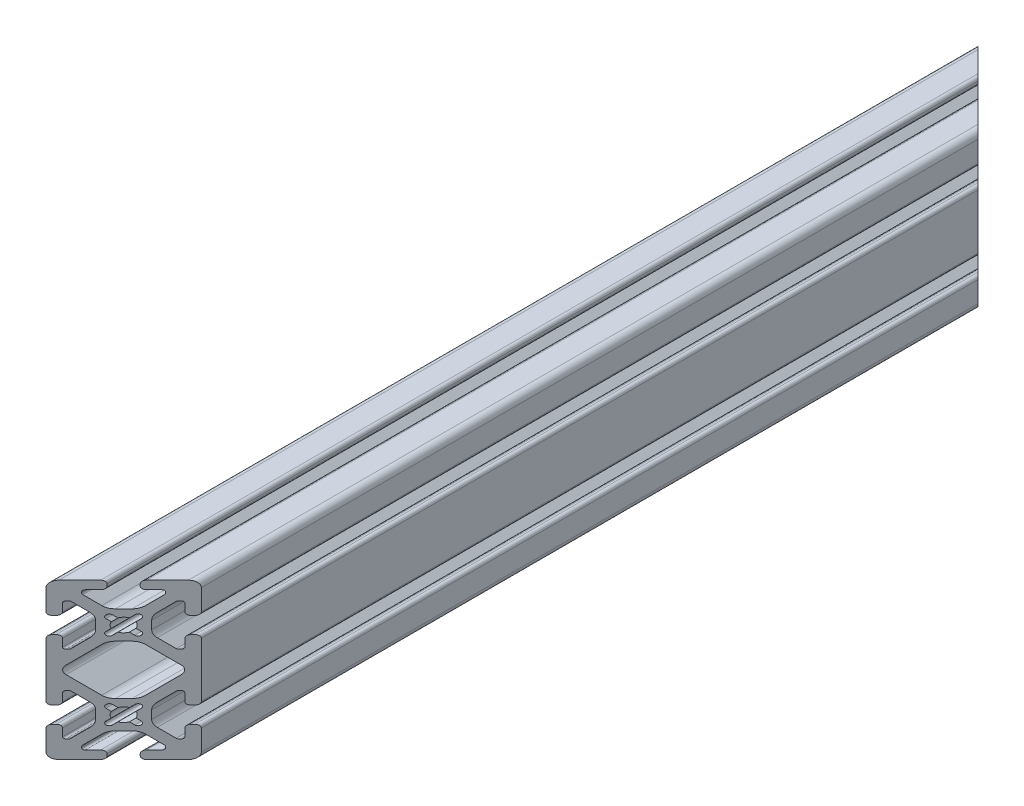
SolidWorks part; units mm, degrees
material "6063-T6"
ref_plane "Front Plane" through (0, 0, 0) normal (0, 0, 1) x (1, 0, 0)
ref_plane "Top Plane" through (0, 0, 0) normal (0, 1, 0) x (1, 0, 0)
ref_plane "Right Plane" through (0, 0, 0) normal (1, 0, 0) x (0, 0, -1)
ref_plane "Plane1" through (0, 0, -25.4) normal (0, 0, -1) x (-1, 0, 0)
sketch "Sketch1" plane through (0, 0, -25.4) normal (0, 0, -1) x (-1, 0, 0)
  line L0 (5.3872, 29.8392) -> (14.1109, 21.1155)
  line L1 (14.1109, 16.9845) -> (5.3872, 8.2608)
  line L2 (2.0285, 6.8697) -> (-2.0285, 6.8697)
  line L3 (-5.3872, 8.2608) -> (-14.1109, 16.9845)
  line L4 (-14.1109, 21.1155) -> (-5.3872, 29.8392)
  line L5 (-2.0285, 31.2303) -> (2.0285, 31.2303)
  line L6 (1.4014, 3.0179) -> (2.7269, 4.3433)
  line L7 (4.3433, 2.7269) -> (3.0179, 1.4014)
  line L8 (3.0179, -1.4014) -> (4.3433, -2.7269)
  line L9 (2.7269, -4.3433) -> (1.4014, -3.0179)
  line L10 (-1.4014, -3.0179) -> (-2.7269, -4.3433)
  line L11 (-4.3433, -2.7269) -> (-3.0179, -1.4014)
  line L12 (-3.0179, 1.4014) -> (-4.3433, 2.7269)
  line L13 (-2.7269, 4.3433) -> (-1.4014, 3.0179)
  line L14 (3.0179, 36.6986) -> (4.3433, 35.3731)
  line L15 (2.7269, 33.7567) -> (1.4014, 35.0821)
  line L16 (-1.4014, 35.0821) -> (-2.7269, 33.7567)
  line L17 (-4.3433, 35.3731) -> (-3.0179, 36.6986)
  line L18 (-3.0179, 39.5014) -> (-4.3433, 40.8269)
  line L19 (-2.7269, 42.4433) -> (-1.4014, 41.1179)
  line L20 (1.4014, 41.1179) -> (2.7269, 42.4433)
  line L21 (4.3433, 40.8269) -> (3.0179, 39.5014)
  line L22 (17.4752, 34.036) -> (16.5608, 34.036)
  line L23 (14.986, 32.4612) -> (14.986, 28.702)
  line L24 (14.097, 27.813) -> (13.5289, 27.813)
  line L25 (12.9003, 28.0734) -> (8.2608, 32.7128)
  line L26 (6.8697, 36.0715) -> (6.8697, 40.1285)
  line L27 (8.2608, 43.4872) -> (12.9003, 48.1266)
  line L28 (13.5289, 48.387) -> (14.097, 48.387)
  line L29 (14.986, 47.498) -> (14.986, 43.7388)
  line L30 (16.5608, 42.164) -> (17.4752, 42.164)
  line L31 (19.05, 43.7388) -> (19.05, 53.975)
  line L32 (15.875, 57.15) -> (5.6388, 57.15)
  line L33 (4.064, 55.5752) -> (4.064, 54.6608)
  line L34 (5.6388, 53.086) -> (9.398, 53.086)
  line L35 (10.287, 52.197) -> (10.287, 51.6289)
  line L36 (10.0266, 51.0003) -> (5.3872, 46.3608)
  line L37 (2.0285, 44.9697) -> (-2.0285, 44.9697)
  line L38 (-5.3872, 46.3608) -> (-10.0266, 51.0003)
  line L39 (-10.287, 51.6289) -> (-10.287, 52.197)
  line L40 (-9.398, 53.086) -> (-5.6388, 53.086)
  line L41 (-4.064, 54.6608) -> (-4.064, 55.5752)
  line L42 (-5.6388, 57.15) -> (-15.875, 57.15)
  line L43 (-19.05, 53.975) -> (-19.05, 43.7388)
  line L44 (-17.4752, 42.164) -> (-16.5608, 42.164)
  line L45 (-14.986, 43.7388) -> (-14.986, 47.498)
  line L46 (-14.097, 48.387) -> (-13.5289, 48.387)
  line L47 (-12.9003, 48.1266) -> (-8.2608, 43.4872)
  line L48 (-6.8697, 40.1285) -> (-6.8697, 36.0715)
  line L49 (-8.2608, 32.7128) -> (-12.9003, 28.0734)
  line L50 (-13.5289, 27.813) -> (-14.097, 27.813)
  line L51 (-14.986, 28.702) -> (-14.986, 32.4612)
  line L52 (-16.5608, 34.036) -> (-17.4752, 34.036)
  line L53 (-19.05, 32.4612) -> (-19.05, 5.6388)
  line L54 (-17.4752, 4.064) -> (-16.5608, 4.064)
  line L55 (-14.986, 5.6388) -> (-14.986, 9.398)
  line L56 (-14.097, 10.287) -> (-13.5289, 10.287)
  line L57 (-12.9003, 10.0266) -> (-8.2608, 5.3872)
  line L58 (-6.8697, 2.0285) -> (-6.8697, -2.0285)
  line L59 (-8.2608, -5.3872) -> (-12.9003, -10.0266)
  line L60 (-13.5289, -10.287) -> (-14.097, -10.287)
  line L61 (-14.986, -9.398) -> (-14.986, -5.6388)
  line L62 (-16.5608, -4.064) -> (-17.4752, -4.064)
  line L63 (-19.05, -5.6388) -> (-19.05, -15.875)
  line L64 (-15.875, -19.05) -> (-5.6388, -19.05)
  line L65 (-4.064, -17.4752) -> (-4.064, -16.5608)
  line L66 (-5.6388, -14.986) -> (-9.398, -14.986)
  line L67 (-10.287, -14.097) -> (-10.287, -13.5289)
  line L68 (-10.0266, -12.9003) -> (-5.3872, -8.2608)
  line L69 (-2.0285, -6.8697) -> (2.0285, -6.8697)
  line L70 (5.3872, -8.2608) -> (10.0266, -12.9003)
  line L71 (10.287, -13.5289) -> (10.287, -14.097)
  line L72 (9.398, -14.986) -> (5.6388, -14.986)
  line L73 (4.064, -16.5608) -> (4.064, -17.4752)
  line L74 (5.6388, -19.05) -> (15.875, -19.05)
  line L75 (19.05, -15.875) -> (19.05, -5.6388)
  line L76 (17.4752, -4.064) -> (16.5608, -4.064)
  line L77 (14.986, -5.6388) -> (14.986, -9.398)
  line L78 (14.097, -10.287) -> (13.5289, -10.287)
  line L79 (12.9003, -10.0266) -> (8.2608, -5.3872)
  line L80 (6.8697, -2.0285) -> (6.8697, 2.0285)
  line L81 (8.2608, 5.3872) -> (12.9003, 10.0266)
  line L82 (13.5289, 10.287) -> (14.097, 10.287)
  line L83 (14.986, 9.398) -> (14.986, 5.6388)
  line L84 (16.5608, 4.064) -> (17.4752, 4.064)
  line L85 (19.05, 5.6388) -> (19.05, 32.4612)
  arc A0 (14.1109, 21.1155) -> (14.1109, 16.9845) centre (12.0454, 19.05) cw
  arc A1 (5.3872, 8.2608) -> (2.0285, 6.8697) centre (2.0285, 11.6195) cw
  arc A2 (-2.0285, 6.8697) -> (-5.3872, 8.2608) centre (-2.0285, 11.6195) cw
  arc A3 (-14.1109, 16.9845) -> (-14.1109, 21.1155) centre (-12.0454, 19.05) cw
  arc A4 (-5.3872, 29.8392) -> (-2.0285, 31.2303) centre (-2.0285, 26.4805) cw
  arc A5 (2.0285, 31.2303) -> (5.3872, 29.8392) centre (2.0285, 26.4805) cw
  arc A6 (2.7269, 4.3433) -> (4.3433, 2.7269) centre (3.5351, 3.5351) cw
  arc A7 (3.0179, 1.4014) -> (3.0179, -1.4014) centre (0, 0) cw
  arc A8 (4.3433, -2.7269) -> (2.7269, -4.3433) centre (3.5351, -3.5351) cw
  arc A9 (1.4014, -3.0179) -> (-1.4014, -3.0179) centre (0, 0) cw
  arc A10 (-2.7269, -4.3433) -> (-4.3433, -2.7269) centre (-3.5351, -3.5351) cw
  arc A11 (-3.0179, -1.4014) -> (-3.0179, 1.4014) centre (0, 0) cw
  arc A12 (-4.3433, 2.7269) -> (-2.7269, 4.3433) centre (-3.5351, 3.5351) cw
  arc A13 (-1.4014, 3.0179) -> (1.4014, 3.0179) centre (0, 0) cw
  arc A14 (4.3433, 35.3731) -> (2.7269, 33.7567) centre (3.5351, 34.5649) cw
  arc A15 (1.4014, 35.0821) -> (-1.4014, 35.0821) centre (0, 38.1) cw
  arc A16 (-2.7269, 33.7567) -> (-4.3433, 35.3731) centre (-3.5351, 34.5649) cw
  arc A17 (-3.0179, 36.6986) -> (-3.0179, 39.5014) centre (0, 38.1) cw
  arc A18 (-4.3433, 40.8269) -> (-2.7269, 42.4433) centre (-3.5351, 41.6351) cw
  arc A19 (-1.4014, 41.1179) -> (1.4014, 41.1179) centre (0, 38.1) cw
  arc A20 (2.7269, 42.4433) -> (4.3433, 40.8269) centre (3.5351, 41.6351) cw
  arc A21 (3.0179, 39.5014) -> (3.0179, 36.6986) centre (0, 38.1) cw
  arc A22 (19.05, 32.4612) -> (17.4752, 34.036) centre (17.4752, 32.4612) ccw
  arc A23 (16.5608, 34.036) -> (14.986, 32.4612) centre (16.5608, 32.4612) ccw
  arc A24 (14.986, 28.702) -> (14.097, 27.813) centre (14.097, 28.702) cw
  arc A25 (13.5289, 27.813) -> (12.9003, 28.0734) centre (13.5289, 28.702) cw
  arc A26 (8.2608, 32.7128) -> (6.8697, 36.0715) centre (11.6195, 36.0715) cw
  arc A27 (6.8697, 40.1285) -> (8.2608, 43.4872) centre (11.6195, 40.1285) cw
  arc A28 (12.9003, 48.1266) -> (13.5289, 48.387) centre (13.5289, 47.498) cw
  arc A29 (14.097, 48.387) -> (14.986, 47.498) centre (14.097, 47.498) cw
  arc A30 (14.986, 43.7388) -> (16.5608, 42.164) centre (16.5608, 43.7388) ccw
  arc A31 (17.4752, 42.164) -> (19.05, 43.7388) centre (17.4752, 43.7388) ccw
  arc A32 (19.05, 53.975) -> (15.875, 57.15) centre (15.875, 53.975) ccw
  arc A33 (5.6388, 57.15) -> (4.064, 55.5752) centre (5.6388, 55.5752) ccw
  arc A34 (4.064, 54.6608) -> (5.6388, 53.086) centre (5.6388, 54.6608) ccw
  arc A35 (9.398, 53.086) -> (10.287, 52.197) centre (9.398, 52.197) cw
  arc A36 (10.287, 51.6289) -> (10.0266, 51.0003) centre (9.398, 51.6289) cw
  arc A37 (5.3872, 46.3608) -> (2.0285, 44.9697) centre (2.0285, 49.7195) cw
  arc A38 (-2.0285, 44.9697) -> (-5.3872, 46.3608) centre (-2.0285, 49.7195) cw
  arc A39 (-10.0266, 51.0003) -> (-10.287, 51.6289) centre (-9.398, 51.6289) cw
  arc A40 (-10.287, 52.197) -> (-9.398, 53.086) centre (-9.398, 52.197) cw
  arc A41 (-5.6388, 53.086) -> (-4.064, 54.6608) centre (-5.6388, 54.6608) ccw
  arc A42 (-4.064, 55.5752) -> (-5.6388, 57.15) centre (-5.6388, 55.5752) ccw
  arc A43 (-15.875, 57.15) -> (-19.05, 53.975) centre (-15.875, 53.975) ccw
  arc A44 (-19.05, 43.7388) -> (-17.4752, 42.164) centre (-17.4752, 43.7388) ccw
  arc A45 (-16.5608, 42.164) -> (-14.986, 43.7388) centre (-16.5608, 43.7388) ccw
  arc A46 (-14.986, 47.498) -> (-14.097, 48.387) centre (-14.097, 47.498) cw
  arc A47 (-13.5289, 48.387) -> (-12.9003, 48.1266) centre (-13.5289, 47.498) cw
  arc A48 (-8.2608, 43.4872) -> (-6.8697, 40.1285) centre (-11.6195, 40.1285) cw
  arc A49 (-6.8697, 36.0715) -> (-8.2608, 32.7128) centre (-11.6195, 36.0715) cw
  arc A50 (-12.9003, 28.0734) -> (-13.5289, 27.813) centre (-13.5289, 28.702) cw
  arc A51 (-14.097, 27.813) -> (-14.986, 28.702) centre (-14.097, 28.702) cw
  arc A52 (-14.986, 32.4612) -> (-16.5608, 34.036) centre (-16.5608, 32.4612) ccw
  arc A53 (-17.4752, 34.036) -> (-19.05, 32.4612) centre (-17.4752, 32.4612) ccw
  arc A54 (-19.05, 5.6388) -> (-17.4752, 4.064) centre (-17.4752, 5.6388) ccw
  arc A55 (-16.5608, 4.064) -> (-14.986, 5.6388) centre (-16.5608, 5.6388) ccw
  arc A56 (-14.986, 9.398) -> (-14.097, 10.287) centre (-14.097, 9.398) cw
  arc A57 (-13.5289, 10.287) -> (-12.9003, 10.0266) centre (-13.5289, 9.398) cw
  arc A58 (-8.2608, 5.3872) -> (-6.8697, 2.0285) centre (-11.6195, 2.0285) cw
  arc A59 (-6.8697, -2.0285) -> (-8.2608, -5.3872) centre (-11.6195, -2.0285) cw
  arc A60 (-12.9003, -10.0266) -> (-13.5289, -10.287) centre (-13.5289, -9.398) cw
  arc A61 (-14.097, -10.287) -> (-14.986, -9.398) centre (-14.097, -9.398) cw
  arc A62 (-14.986, -5.6388) -> (-16.5608, -4.064) centre (-16.5608, -5.6388) ccw
  arc A63 (-17.4752, -4.064) -> (-19.05, -5.6388) centre (-17.4752, -5.6388) ccw
  arc A64 (-19.05, -15.875) -> (-15.875, -19.05) centre (-15.875, -15.875) ccw
  arc A65 (-5.6388, -19.05) -> (-4.064, -17.4752) centre (-5.6388, -17.4752) ccw
  arc A66 (-4.064, -16.5608) -> (-5.6388, -14.986) centre (-5.6388, -16.5608) ccw
  arc A67 (-9.398, -14.986) -> (-10.287, -14.097) centre (-9.398, -14.097) cw
  arc A68 (-10.287, -13.5289) -> (-10.0266, -12.9003) centre (-9.398, -13.5289) cw
  arc A69 (-5.3872, -8.2608) -> (-2.0285, -6.8697) centre (-2.0285, -11.6195) cw
  arc A70 (2.0285, -6.8697) -> (5.3872, -8.2608) centre (2.0285, -11.6195) cw
  arc A71 (10.0266, -12.9003) -> (10.287, -13.5289) centre (9.398, -13.5289) cw
  arc A72 (10.287, -14.097) -> (9.398, -14.986) centre (9.398, -14.097) cw
  arc A73 (5.6388, -14.986) -> (4.064, -16.5608) centre (5.6388, -16.5608) ccw
  arc A74 (4.064, -17.4752) -> (5.6388, -19.05) centre (5.6388, -17.4752) ccw
  arc A75 (15.875, -19.05) -> (19.05, -15.875) centre (15.875, -15.875) ccw
  arc A76 (19.05, -5.6388) -> (17.4752, -4.064) centre (17.4752, -5.6388) ccw
  arc A77 (16.5608, -4.064) -> (14.986, -5.6388) centre (16.5608, -5.6388) ccw
  arc A78 (14.986, -9.398) -> (14.097, -10.287) centre (14.097, -9.398) cw
  arc A79 (13.5289, -10.287) -> (12.9003, -10.0266) centre (13.5289, -9.398) cw
  arc A80 (8.2608, -5.3872) -> (6.8697, -2.0285) centre (11.6195, -2.0285) cw
  arc A81 (6.8697, 2.0285) -> (8.2608, 5.3872) centre (11.6195, 2.0285) cw
  arc A82 (12.9003, 10.0266) -> (13.5289, 10.287) centre (13.5289, 9.398) cw
  arc A83 (14.097, 10.287) -> (14.986, 9.398) centre (14.097, 9.398) cw
  arc A84 (14.986, 5.6388) -> (16.5608, 4.064) centre (16.5608, 5.6388) ccw
  arc A85 (17.4752, 4.064) -> (19.05, 5.6388) centre (17.4752, 5.6388) ccw
extrude "Boss-Extrude1" add sketch "Sketch1" against normal blind 457.2
sketch "Sketch2" plane through (0, -19.05, 0) normal (0, -1, 0) x (1, 0, 0)
  line L0 (-19.05, -25.4) -> (19.05, 12.7)
  line L1 (19.05, 431.8) -> (19.05, -25.4) construction
  line L2 (19.05, 12.7) -> (19.05, -25.4)
  line L3 (19.05, -25.4) -> (-19.05, -25.4)
  line L4 (19.05, 393.7) -> (-19.05, 431.8)
  line L5 (-19.05, 431.8) -> (19.05, 431.8)
  line L6 (19.05, 431.8) -> (19.05, 393.7)
  line L7 (-19.05, 431.8) -> (-19.05, -25.4) construction
  dimension "D1" = 45
  dimension "D2" = 45
extrude "Cut-Extrude1" cut sketch "Sketch2" against normal up to next
